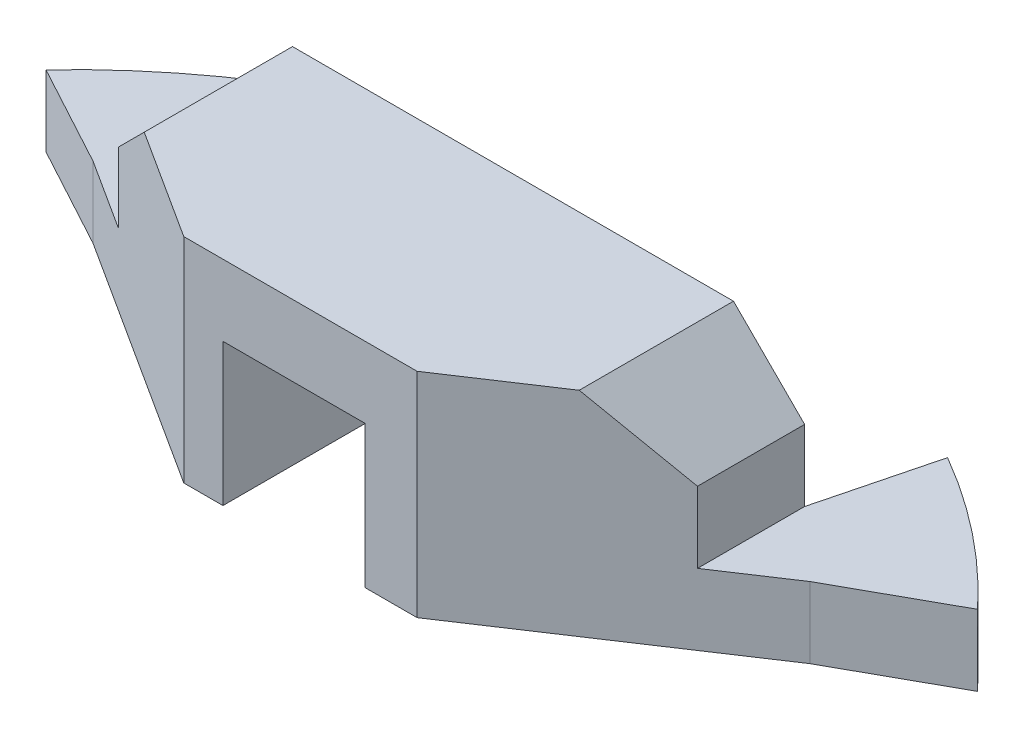
SolidWorks part; units mm, degrees
ref_plane "Front Plane" through (0, 0, 0) normal (0, 0, 1) x (1, 0, 0)
ref_plane "Top Plane" through (0, 0, 0) normal (0, 1, 0) x (1, 0, 0)
ref_plane "Right Plane" through (0, 0, 0) normal (1, 0, 0) x (0, 0, -1)
sketch "Sketch1" plane through (0, 0, 0) normal (0, 1, 0) x (1, 0, 0)
  line L60 (-65.4953, 61.7282) -> (-51.0649, 53.9134)
  line L61 (-51.0649, 53.9134) -> (-15.5104, 31.112)
  line L62 (-15.5104, 31.112) -> (17.2885, 31.112)
  line L63 (17.2885, 31.112) -> (50.5104, 53.129)
  line L73 (50.5104, 53.129) -> (65.6763, 61.5356)
  line L80 (-45.0961, 77.8867) -> (-41, 61.8867)
  line L82 (-41, 61.8867) -> (41, 61.8867)
  line L83 (45.0961, 77.8867) -> (41, 61.8867)
  arc A0 (65.6763, 61.5356) -> (45.0961, 77.8867) centre (0, 0) ccw
  arc A24 (-45.0961, 77.8867) -> (-65.4953, 61.7282) centre (0, 0) ccw
extrude "Boss-Extrude1" add sketch "Sketch1" along normal blind 30
sketch "Sketch3" plane through (0, 30, 0) normal (0, 1, 0) x (1, 0, 0)
  line L0 (41, 61.8867) -> (41, 39.992)
  line L1 (41, 39.992) -> (77.2605, 39.992)
  line L2 (77.2605, 39.992) -> (80.6025, 99.0848)
  line L3 (80.6025, 99.0848) -> (39.7389, 90.426)
  line L4 (39.7389, 90.426) -> (41, 61.8867)
extrude "Cut-Extrude1" cut sketch "Sketch3" against normal blind 20
mirror "Mirror1" about plane through (0, 0, 0) normal (1, 0, 0) of "Cut-Extrude1"
chamfer "Chamfer1" distance 10 angle 45 2 edges at (41, 30, -54.3565) (-41, 30, -54.6727)
sketch "Sketch4" plane through (0, 0, -61.8867) normal (0, 0, -1) x (-1, 0, 0)
  line L1 (-10, 20) -> (10, 20)
  line L2 (-10, 20) -> (-10, 0)
  line L3 (-10, 0) -> (10, 0)
  line L4 (10, 20) -> (10, 0)
  line L5 (-10, 20) -> (10, 0) construction
  line L6 (-10, 0) -> (10, 20) construction
  point P0 (0, 10)
  point P6 (0, 0)
  dimension "D1" = 20
  dimension "D2" = 20
extrude "Cut-Extrude2" cut sketch "Sketch4" against normal blind 41.3583
